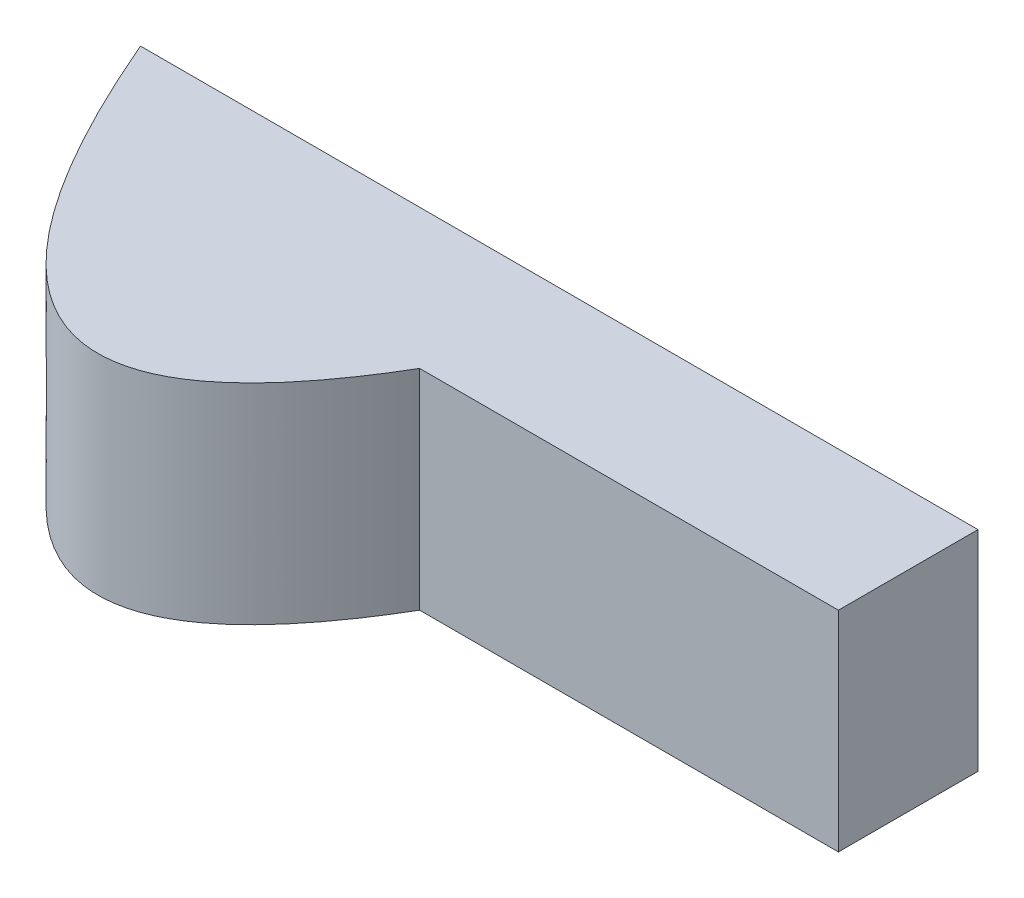
SolidWorks part; units mm, degrees
ref_plane "Alzado" through (0, 0, 0) normal (0, 0, 1) x (1, 0, 0)
ref_plane "Planta" through (0, 0, 0) normal (0, 1, 0) x (1, 0, 0)
ref_plane "Vista lateral" through (0, 0, 0) normal (1, 0, 0) x (0, 0, -1)
sketch "Croquis2" plane through (0, 0, 0) normal (0, 1, 0) x (1, 0, 0)
  line L0 (-200, 70) -> (200, 70)
  line L1 (-200, 70) -> (-200, -70)
  line L2 (-200, -70) -> (200, -70)
  line L3 (200, 70) -> (200, -70)
  line L4 (0, 70) -> (60, 70)
  line L5 (0, 70) -> (0, -70)
  line L6 (0, -70) -> (60, -70)
  line L7 (60, 70) -> (60, -70)
  line L8 (200, 70) -> (120, 70)
  line L9 (200, 70) -> (200, 50)
  line L10 (200, 50) -> (120, 50)
  line L11 (0, 70) -> (-60, 70)
  line L12 (0, 70) -> (0, 50)
  line L13 (0, 50) -> (-60, 50)
  line L14 (-60, 60.1561) -> (-60, 50)
  spline S0 degree 2 poles (60, 70) (89.7639, -0.5628) (120, 50) knots 0 0 0 1 1 1
  spline S1 degree 2 poles (-120, 70) (-89.7132, -0.7337) (-60, 50) knots 0 0 0 1 1 1
  point P14 (99.6856, 29.6804)
  point P15 (60, 70)
  point P16 (120, 50)
  point P18 (-120, 70)
  point P19 (-60, 50)
  point P20 (-79.8536, 29.6804)
extrude "Saliente-Extruir5" add sketch "Croquis2" along normal blind 30
sketch "Croquis6" plane through (0, 30, 0) normal (0, 1, 0) x (1, 0, 0)
  line L6 (-61.4436, 52.5) -> (-2.5, 52.5)
  line L7 (-2.5, 52.5) -> (-2.5, 67.5)
  line L8 (-2.5, 67.5) -> (-116.1771, 67.5)
  line L9 (-61.4436, 52.5) -> (-2.5, 52.5)
  line L10 (-2.5, 52.5) -> (-2.5, 67.5)
  line L11 (-2.5, 67.5) -> (-116.1771, 67.5)
  spline S0 degree 3 poles (-2889.6565, -1004.4848) (-36.4072, 489.2017) (-188.1193, 206.2802) (-110.1592, 55.1761) (-108.4948, 52.1897) (-105.7747, 47.8423) (-104.8303, 46.4154) (-102.8405, 43.6214) (-101.7956, 42.2539) (-100.1201, 40.2667) (-99.5427, 39.6145) (-98.3549, 38.3496) (-97.7435, 37.7355) (-96.4773, 36.5523) (-95.8227, 35.9831) (-94.4585, 34.902) (-93.7543, 34.3946) (-92.3007, 33.469) (-91.5501, 33.0496) (-90.3785, 32.5039) (-89.9804, 32.3359) (-89.1664, 32.0322) (-88.7482, 31.8959) (-87.4852, 31.5487) (-86.632, 31.3986) (-85.3333, 31.3092) (-84.8968, 31.3021) (-84.0191, 31.3352) (-83.5851, 31.3751) (-82.2964, 31.5603) (-81.4553, 31.771) (-80.217, 32.2004) (-79.8088, 32.3624) (-79.0135, 32.7147) (-78.6244, 32.9055) (-77.4799, 33.5164) (-76.7467, 33.9747) (-75.3273, 34.9713) (-74.6386, 35.5122) (-72.6601, 37.2055) (-71.4477, 38.4316) (-69.1582, 41.0072) (-68.0823, 42.3578) (-66.5418, 44.4508) (-66.0408, 45.1598) (-65.0642, 46.5915) (-64.588, 47.3151) (0.4417, 149.2744) (-135.2674, 377.4801) (2632.8049, -1235.3626) knots -5.958251 -5.958251 -5.958251 -5.958251 0.125 0.125 0.25 0.25 0.3125 0.3125 0.375 0.375 0.40625 0.40625 0.4375 0.4375 0.46875 0.46875 0.5 0.5 0.53125 0.53125 0.546875 0.546875 0.5625 0.5625 0.59375 0.59375 0.609375 0.609375 0.625 0.625 0.65625 0.65625 0.671875 0.671875 0.6875 0.6875 0.71875 0.71875 0.75 0.75 0.8125 0.8125 0.875 0.875 0.90625 0.90625 0.9375 0.9375 5.269657 5.269657 5.269657 5.269657 only from (-116.1771, 67.5) to (-61.4436, 52.5)
  spline S1 degree 3 poles (-116.1771, 67.5) (-114.7719, 64.3603) (-113.2986, 61.261) (-110.1592, 55.1761) (-108.4948, 52.1897) (-105.7747, 47.8423) (-104.8303, 46.4154) (-102.8405, 43.6214) (-101.7956, 42.2539) (-100.1201, 40.2667) (-99.5427, 39.6145) (-98.3549, 38.3496) (-97.7435, 37.7355) (-96.4773, 36.5523) (-95.8227, 35.9831) (-94.4585, 34.902) (-93.7543, 34.3946) (-92.3007, 33.469) (-91.5501, 33.0496) (-90.3785, 32.5039) (-89.9804, 32.3359) (-89.1664, 32.0322) (-88.7482, 31.8959) (-87.4852, 31.5487) (-86.632, 31.3986) (-85.3333, 31.3092) (-84.8968, 31.3021) (-84.0191, 31.3352) (-83.5851, 31.3751) (-82.2964, 31.5603) (-81.4553, 31.771) (-80.217, 32.2004) (-79.8088, 32.3624) (-79.0135, 32.7147) (-78.6244, 32.9055) (-77.4799, 33.5164) (-76.7467, 33.9747) (-75.3273, 34.9713) (-74.6386, 35.5122) (-72.6601, 37.2055) (-71.4477, 38.4316) (-69.1582, 41.0072) (-68.0823, 42.3578) (-66.5418, 44.4508) (-66.0408, 45.1598) (-65.0642, 46.5915) (-64.588, 47.3151) (-63.1908, 49.5058) (-62.301, 50.9926) (-61.4436, 52.5) knots 0 0 0 0 0.125 0.125 0.25 0.25 0.3125 0.3125 0.375 0.375 0.40625 0.40625 0.4375 0.4375 0.46875 0.46875 0.5 0.5 0.53125 0.53125 0.546875 0.546875 0.5625 0.5625 0.59375 0.59375 0.609375 0.609375 0.625 0.625 0.65625 0.65625 0.671875 0.671875 0.6875 0.6875 0.71875 0.71875 0.75 0.75 0.8125 0.8125 0.875 0.875 0.90625 0.90625 0.9375 0.9375 1 1 1 1
  dimension "D1" = 2.5
extrude "Cortar-Extruir3" cut sketch "Croquis6" against normal through all from offset 2.5
